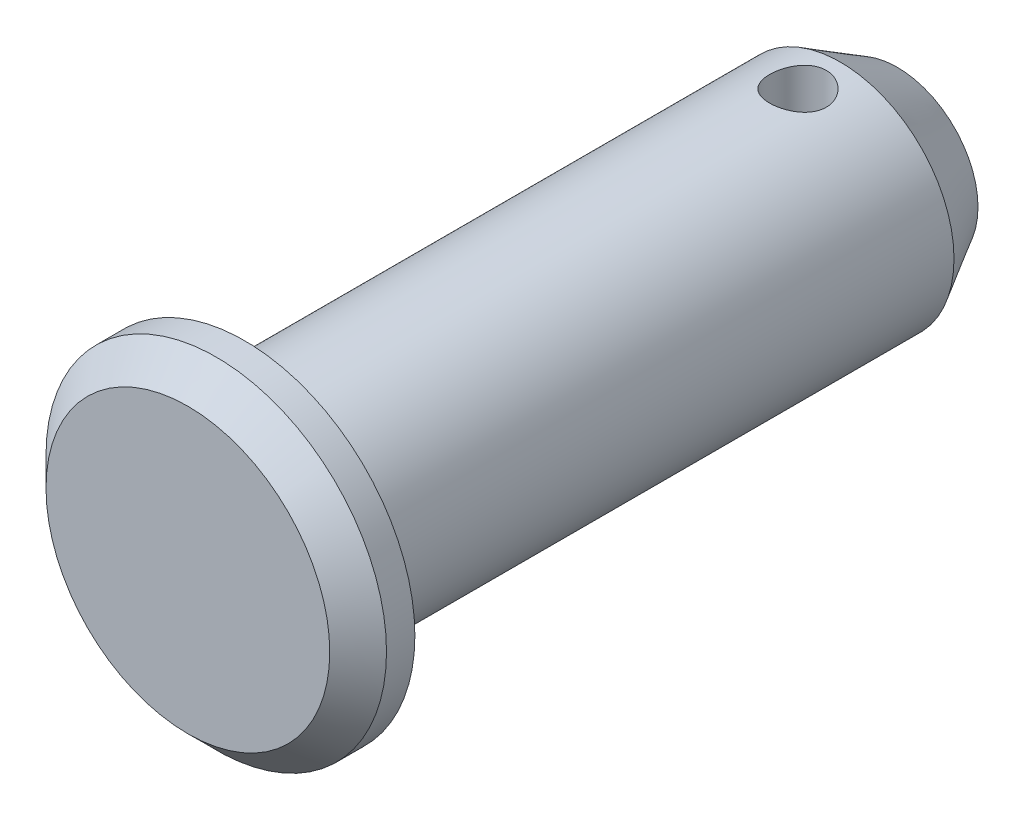
SolidWorks part; units mm, degrees
material "1.0545 (S355N)"
ref_plane "Płaszczyzna przednia" through (0, 0, 0) normal (0, 0, 1) x (1, 0, 0)
ref_plane "Płaszczyzna górna" through (0, 0, 0) normal (0, 1, 0) x (1, 0, 0)
ref_plane "Płaszczyzna prawa" through (0, 0, 0) normal (1, 0, 0) x (0, 0, -1)
sketch "Szkic1" plane through (0, 0, 0) normal (0, 1, 0) x (1, 0, 0)
  line L0 (5, -12.5) -> (-5, -12.5)
  line L1 (-6, -11.5) -> (-6, -10.5)
  line L2 (-6, -10.5) -> (-4, -10.5)
  line L3 (-4, -10.5) -> (-4, 10.5)
  line L4 (-2.8453, 12.5) -> (2.8453, 12.5)
  line L5 (4, 10.5) -> (4, -10.5)
  line L6 (4, -10.5) -> (6, -10.5)
  line L7 (6, -10.5) -> (6, -11.5)
  line L8 (6, -11.5) -> (5, -12.5)
  line L9 (-5, -12.5) -> (-6, -11.5)
  line L10 (2.8453, 12.5) -> (4, 10.5)
  line L11 (-4, 10.5) -> (-2.8453, 12.5)
  line L12 (0, -12.5) -> (0, 12.5)
  point P0 (6, -12.5)
  point P1 (-6, -12.5)
  point P5 (-4, 12.5)
  point P6 (4, 12.5)
  point P7 (0, 0)
  point P17 (0, 12.5)
  point P19 (0, -12.5)
  dimension "D1" = 12
  dimension "D2" = 8
  dimension "D3" = 2
  dimension "D4" = 30
  dimension "D8" = 30
  dimension "D9" = 23
  dimension "D10" = 2
revolve "Obrót1" add sketch "Szkic1" angle 360 about L12
sketch "Szkic2" plane through (0, 0, 0) normal (0, 1, 0) x (1, 0, 0)
  line L0 (4, -10.5) -> (-4, -10.5) construction
  circle A0 centre (0, 9) radius 1
  dimension "D2" = 2
  dimension "D1" = 19.5
extrude "Wytnij-wyciągnięcie1" cut sketch "Szkic2" against normal through all both and the other way through all contours A0
